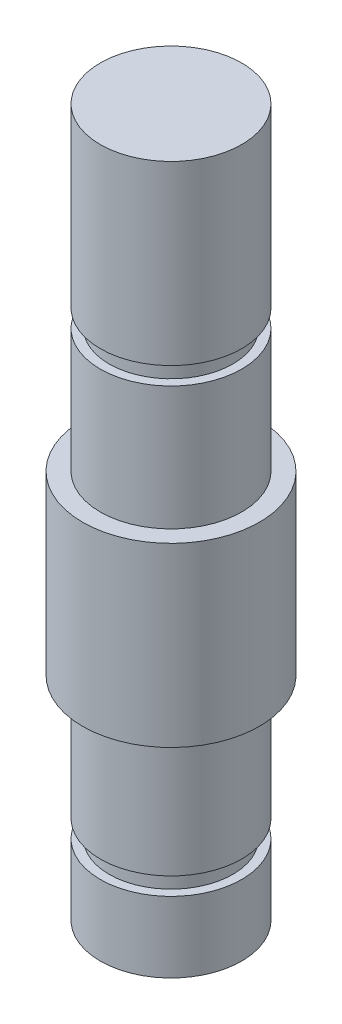
SolidWorks part; units mm, degrees
ref_plane "Front Plane" through (0, 0, 0) normal (0, 0, 1) x (1, 0, 0)
ref_plane "Top Plane" through (0, 0, 0) normal (0, 1, 0) x (1, 0, 0)
ref_plane "Right Plane" through (0, 0, 0) normal (1, 0, 0) x (0, 0, -1)
sketch "Sketch1" plane through (0, 0, 0) normal (0, 1, 0) x (1, 0, 0)
  circle A0 centre (0, 0) radius 5
  dimension "D1" = 10
extrude "Boss-Extrude1" add sketch "Sketch1" along normal mid plane 34
sketch "Sketch2" plane through (0, 17, 0) normal (0, 1, 0) x (1, 0, 0)
  circle A0 centre (0, 0) radius 5
  circle A1 centre (0, 0) radius 4
  dimension "D1" = 8
extrude "Cut-Extrude1" cut sketch "Sketch2" against normal blind 12
mirror "Mirror1" about plane through (0, 0, 0) normal (0, 1, 0) of "Cut-Extrude1"
sketch "Sketch3" plane through (0, 17, 0) normal (0, 1, 0) x (1, 0, 0)
  circle A0 centre (0, 0) radius 4
  circle A1 centre (0, 0) radius 3.5
  dimension "D1" = 7
extrude "Cut-Extrude2" cut sketch "Sketch3" against normal blind 1 from offset 4 offset against normal yes
mirror "Mirror2" about plane through (0, 0, 0) normal (0, 1, 0) of "Cut-Extrude2"
sketch "Sketch4" plane through (0, 17, 0) normal (0, 1, 0) x (1, 0, 0)
  circle A0 centre (0, 0) radius 4
extrude "Boss-Extrude2" add sketch "Sketch4" along normal blind 6
